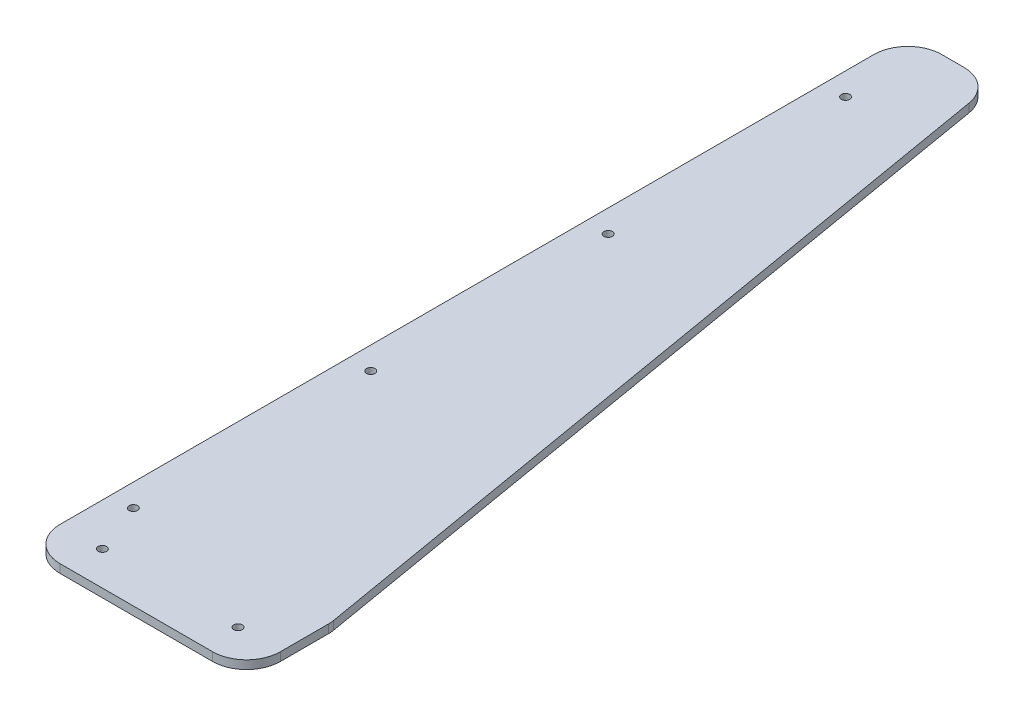
SolidWorks part; units mm, degrees
material "Acrylic (Medium-high impact)"
ref_plane "Front Plane" through (0, 0, 0) normal (0, 0, 1) x (1, 0, 0)
ref_plane "Top Plane" through (0, 0, 0) normal (0, 1, 0) x (1, 0, 0)
ref_plane "Right Plane" through (0, 0, 0) normal (1, 0, 0) x (0, 0, -1)
sketch "Sketch1" plane through (0, 0, 0) normal (0, 1, 0) x (1, 0, 0)
  line L0 (31.75, 0) -> (82.55, 0)
  line L1 (0, 0) -> (31.75, 0)
  line L2 (0, 0) -> (0, 330.2)
  line L3 (0, 330.2) -> (31.75, 330.2)
  line L4 (31.75, 31.75) -> (31.75, 330.2) construction
  line L5 (82.55, 0) -> (82.55, 31.75)
  line L6 (82.55, 31.75) -> (31.75, 31.75) construction
  line L7 (31.75, 330.2) -> (82.55, 31.75)
  dimension "D1" = 330.2
  dimension "D2" = 31.75
  dimension "D3" = 50.8
extrude "Boss-Extrude1" add sketch "Sketch1" along normal blind 3.175
fillet "Fillet1" radius 12.7 5 edges at (82.55, 1.5875, 0) (0, 1.5875, 0) (0, 1.5875, -330.2) (82.55, 1.5875, -31.75) (31.75, 1.5875, -330.2)
hole_wizard "1/8 (0.125) Diameter Hole1" positions "Sketch3" profile "Sketch4" hole size "1/8" standard "ANSI Inch" end condition through all
sketch "Sketch3" plane through (0, 0, 0) normal (0, -1, 0) x (-1, 0, 0)
  line L0 (-8.4328, 298.45) -> (-8.4328, 209.55) construction
  line L1 (-8.4328, 209.55) -> (-8.4328, 120.65) construction
  line L2 (-8.4328, 120.65) -> (-8.4328, 31.75) construction
  line L3 (-8.4328, 31.75) -> (-15.875, 12.7) construction
  line L4 (-15.875, 12.7) -> (-66.675, 12.7) construction
  line L6 (0, 317.5) -> (0, 12.7) construction
  line L7 (-12.7, 0) -> (-69.85, 0) construction
  point P0 (-8.4328, 298.45)
  point P4 (-8.4328, 209.55)
  point P6 (-8.4328, 120.65)
  point P8 (-8.4328, 31.75)
  point P10 (-66.675, 12.7)
  point P12 (-15.875, 12.7)
  point P29 (0, 0)
  point P30 (-15.3597, 16.2942)
  point P32 (-41.275, 12.7)
  point P33 (-41.275, 0)
  dimension "D1" = 88.9
  dimension "D2" = 8.4328
  dimension "D3" = 31.75
  dimension "D4" = 50.8
  dimension "D5" = 12.7
sketch "Sketch4" plane through (8.4328, 0, -298.45) normal (1, 0, 0) x (0, 0, -1)
  line L0 (0, 0) -> (0, 3.175)
  line L1 (0, 3.175) -> (1.5875, 3.175)
  line L2 (1.5875, 3.175) -> (1.5875, 0)
  line L5 (1.5875, 0) -> (0, 0)
  line L11 (0, -6.35) -> (0, 107.95) construction
  dimension "Thru Hole Dia." = 3.175
  dimension "Thru Hole Depth" = 3.175
